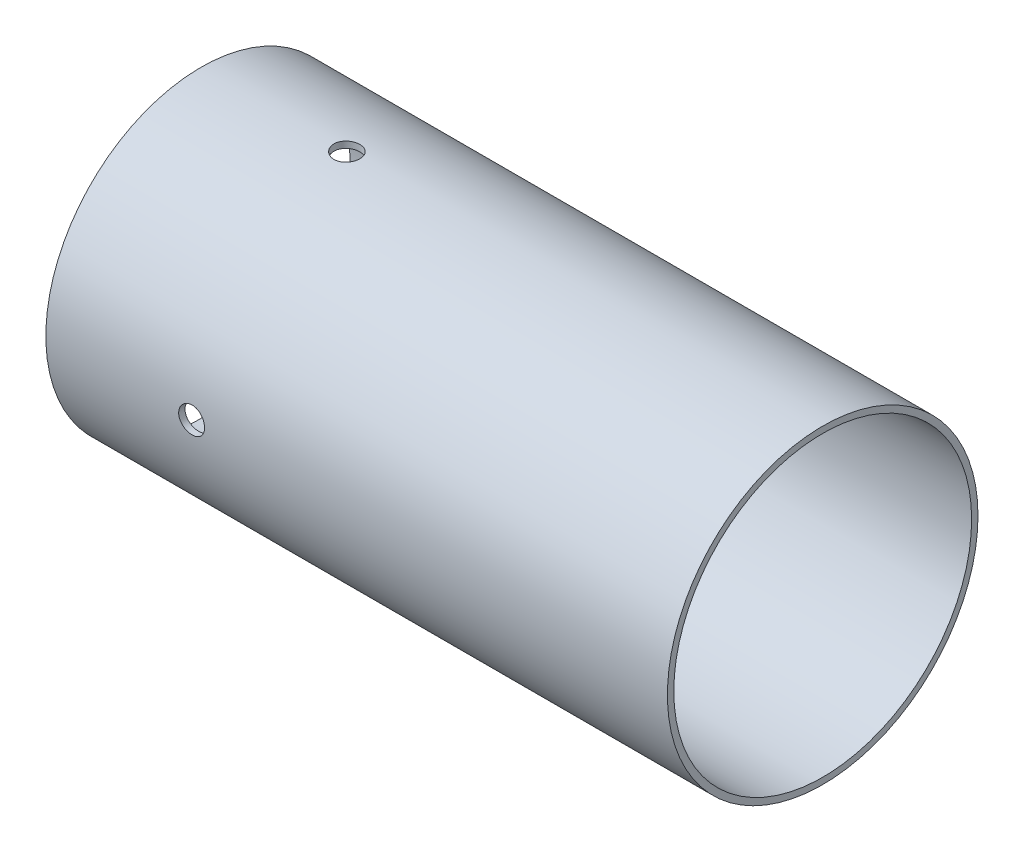
SolidWorks part; units mm, degrees
ref_plane "Front Plane" through (0, 0, 0) normal (1, 0, 0) x (0, 1, 0)
ref_plane "Top Plane" through (0, 0, 0) normal (0, 0, 1) x (0, 1, 0)
ref_plane "Right Plane" through (0, 0, 0) normal (0, 1, 0) x (-1, 0, 0)
sketch "Sketch1" plane through (0, 0, 0) normal (1, 0, 0) x (0, 1, 0)
  circle A0 centre (0, 0) radius 36.5125
  circle A1 centre (0, 0) radius 38.0746
  dimension "D1" = 76.1492
  dimension "D2" = 73.025
extrude "Boss-Extrude1" add sketch "Sketch1" along normal blind 152.4
sketch "Sketch2" plane through (0, 0, 0) normal (0, 1, 0) x (-1, 0, 0)
  circle A0 centre (-35.7378, 0) radius 3.175
  point P4 (0, 0)
  dimension "D1" = 6.35
  dimension "D2" = 35.7378
extrude "Cut-Extrude1" cut sketch "Sketch2" along normal through all
pattern_circular "CirPattern1" count 4 over 360 about axis through (152.4, 0, 0) along (-1, 0, 0) of "Cut-Extrude1"
